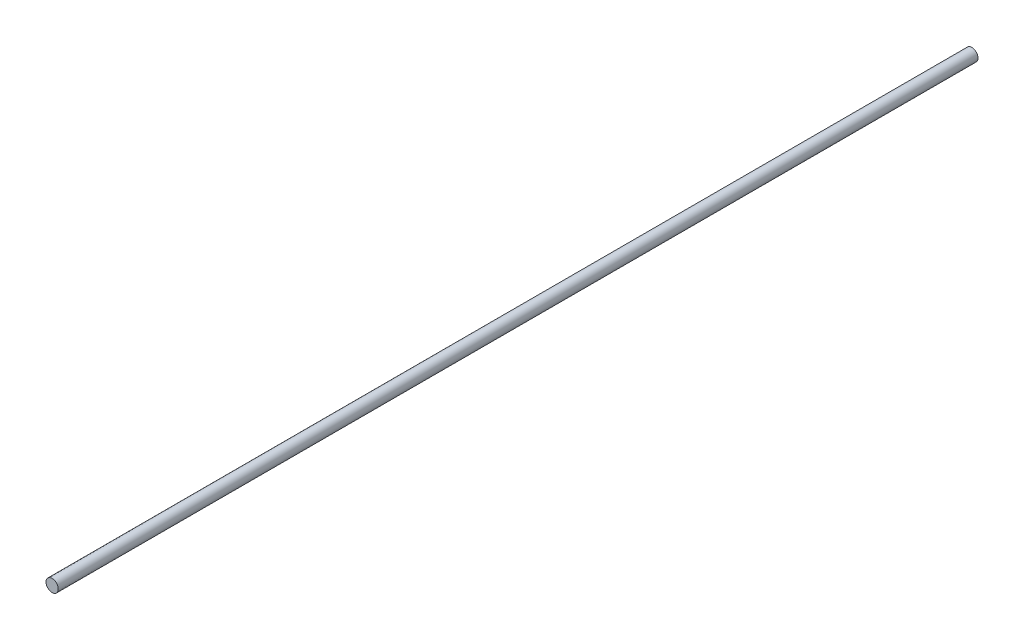
SolidWorks part; units mm, degrees
ref_plane "Front Plane" through (0, 0, 0) normal (0, 0, 1) x (1, 0, 0)
ref_plane "Top Plane" through (0, 0, 0) normal (0, 1, 0) x (1, 0, 0)
ref_plane "Right Plane" through (0, 0, 0) normal (1, 0, 0) x (0, 0, -1)
sketch "Sketch1" plane through (0, 0, 0) normal (0, 0, 1) x (1, 0, 0)
  circle A0 centre (0, 0) radius 2
  dimension "D1" = 4
extrude "Boss-Extrude1" add sketch "Sketch1" along normal blind 300
